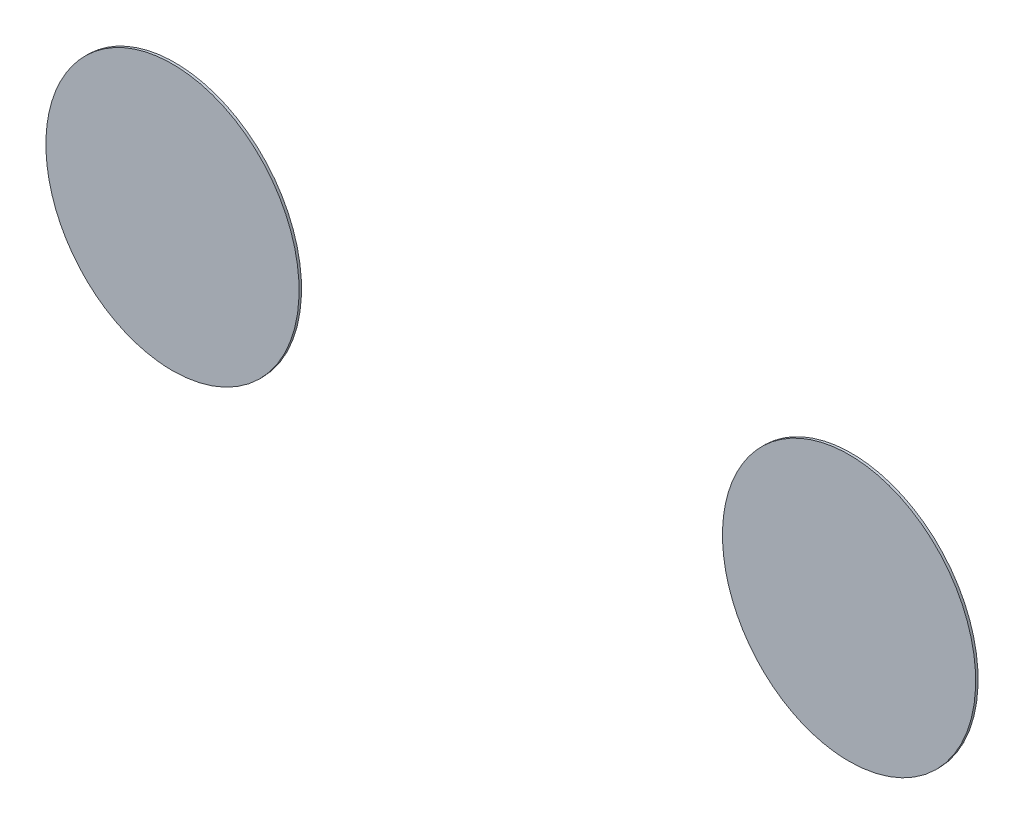
SolidWorks part; units mm, degrees
ref_plane "Front Plane" through (0, 0, 0) normal (0, 0, 1) x (1, 0, 0)
ref_plane "Top Plane" through (0, 0, 0) normal (0, 1, 0) x (1, 0, 0)
ref_plane "Right Plane" through (0, 0, 0) normal (1, 0, 0) x (0, 0, -1)
sketch "Sketch1" plane through (0, 0, 0) normal (0, 0, 1) x (1, 0, 0)
  line L0 (-30.5691, 131.9848) -> (-24.9858, 131.9848) construction
  line L1 (-27.7774, 134.5817) -> (-27.7774, 129.4862) construction
  line L2 (25.8719, 131.9848) -> (29.683, 131.9848) construction
  line L3 (27.7774, 134.5817) -> (27.7774, 129.3878) construction
  ellipse E0 centre (-27.7774, 131.9848) end of major axis (-27.7774, 121.0783) minor radius 10.3952 construction
  ellipse E1 centre (-27.7774, 131.9848) end of major axis (-27.7774, 121.0783) minor radius 10.3952
  ellipse E2 centre (27.7774, 131.9848) end of major axis (27.7774, 121.0783) minor radius 10.3952 construction
  ellipse E3 centre (27.7774, 131.9848) end of major axis (27.7774, 121.0783) minor radius 10.3952
extrude "Boss-Extrude1" add sketch "Sketch1" along normal blind 0.2
ref_point "Point1"
ref_point "Point2"
